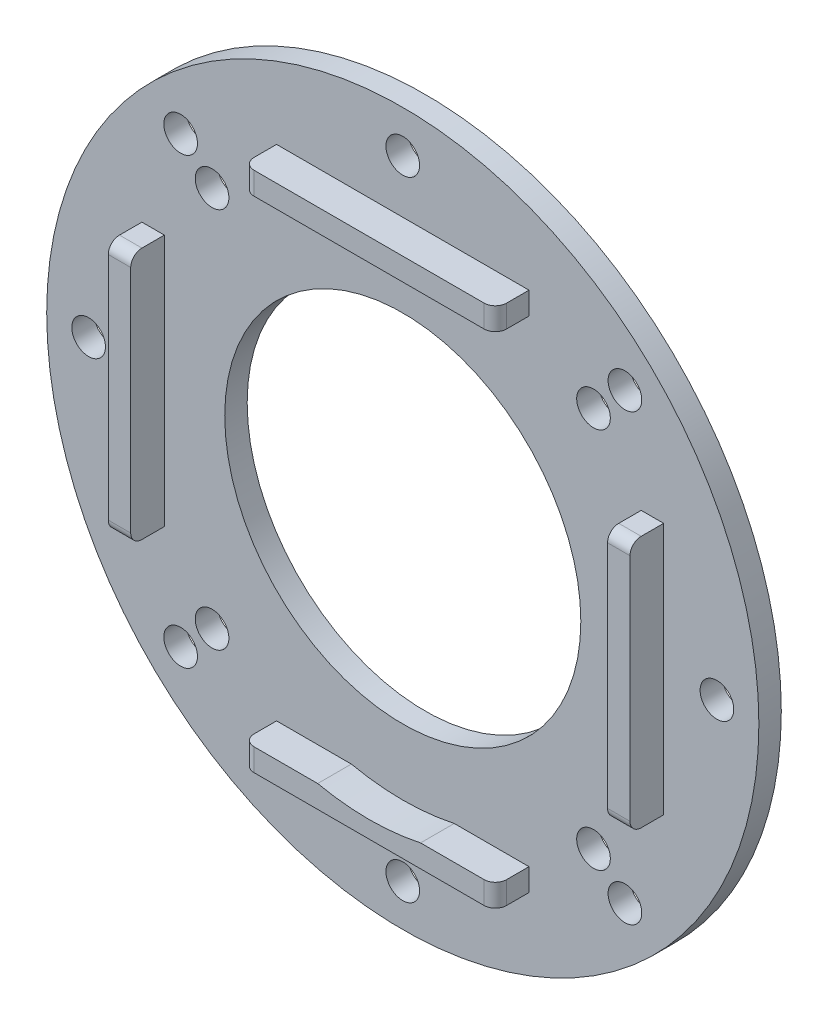
SolidWorks part; units mm, degrees
ref_plane "前视基准面" through (0, 0, 0) normal (0, 0, 1) x (1, 0, 0)
ref_plane "上视基准面" through (0, 0, 0) normal (0, 1, 0) x (1, 0, 0)
ref_plane "右视基准面" through (0, 0, 0) normal (1, 0, 0) x (0, 0, -1)
other "Configuration Table"
sketch "草图1" plane through (0, 0, 0) normal (0, 0, 1) x (1, 0, 0)
  line L1 (-17, -17) -> (17, -17)
  line L2 (-17, -17) -> (-17, 17)
  line L3 (-17, 17) -> (17, 17)
  line L4 (17, -17) -> (17, 17)
  line L5 (-17, -17) -> (17, 17) construction
  line L6 (-17, 17) -> (17, -17) construction
  circle A0 centre (0, 0) radius 31.739
  circle A1 centre (0, 0) radius 15.8695
  circle A2 centre (-17, 17) radius 1.5
  circle A3 centre (17, 17) radius 1.5
  circle A4 centre (17, -17) radius 1.5
  circle A5 centre (-17, -17) radius 1.5
  circle A6 centre (-19.799, 19.799) radius 1.5
  circle A7 centre (0, 28) radius 1.5
  circle A8 centre (19.799, 19.799) radius 1.5
  circle A9 centre (28, 0) radius 1.5
  circle A10 centre (19.799, -19.799) radius 1.5
  circle A11 centre (0, -28) radius 1.5
  circle A12 centre (-19.799, -19.799) radius 1.5
  circle A13 centre (-28, 0) radius 1.5
  point P18 (0, 0)
  point P36 (0, 0)
  dimension "D3" = 4
  dimension "D1" = 34
  dimension "D2" = 34
  dimension "D4" = 8
extrude "凸台-拉伸2" add sketch "草图1" along normal blind 2 contours A0 A13 A12 A11 A10 A9 A8 A7 A6 A5 L2 A2 L3 A3 L4 A4 L1 | A5 L1 A4 L4 A3 L3 A2 L2 A1
sketch "草图2" plane through (0, 0, 2) normal (0, 0, 1) x (1, 0, 0)
  line L0 (-23.25, -23.25) -> (-23.25, 23.25)
  line L1 (-21.25, -21.25) -> (21.25, -21.25)
  line L2 (-21.25, -21.25) -> (-21.25, 21.25)
  line L3 (-21.25, 21.25) -> (21.25, 21.25)
  line L4 (21.25, -21.25) -> (21.25, 21.25)
  line L5 (-21.25, -21.25) -> (21.25, 21.25) construction
  line L6 (-21.25, 21.25) -> (21.25, -21.25) construction
  line L7 (-23.25, 23.25) -> (23.25, 23.25)
  line L8 (23.25, -23.25) -> (23.25, 23.25)
  line L9 (-23.25, -23.25) -> (23.25, -23.25)
  line L10 (-21.25, 21.25) -> (-11.25, 21.25)
  line L11 (-11.25, 21.25) -> (-11.25, 23.25)
  line L12 (21.25, 21.25) -> (11.25, 21.25)
  line L13 (11.25, 21.25) -> (11.25, 23.25)
  line L14 (21.25, 11.25) -> (23.25, 11.25)
  line L15 (23.25, 23.25) -> (23.25, -23.25)
  line L16 (21.25, 21.25) -> (21.25, -21.25)
  line L17 (21.25, -11.25) -> (23.25, -11.25)
  line L18 (11.25, -21.25) -> (11.25, -23.25)
  line L19 (23.25, -23.25) -> (-23.25, -23.25)
  line L20 (21.25, -21.25) -> (-21.25, -21.25)
  line L21 (-11.25, -21.25) -> (-11.25, -23.25)
  line L22 (-21.25, -11.25) -> (-23.25, -11.25)
  line L23 (-23.25, -23.25) -> (-23.25, 23.25)
  line L24 (-21.25, -21.25) -> (-21.25, 21.25)
  line L25 (-21.25, 11.25) -> (-23.25, 11.25)
  circle A2 centre (0, 0) radius 21.739
  circle A3 centre (0, 0) radius 21.739
  point P0 (0, 0)
  point P44 (0, 0)
  dimension "D1" = 42.5
  dimension "D2" = 42.5
  dimension "D4" = 2
  dimension "D5" = 10
  dimension "D6" = 10
  dimension "D3" = 10
  dimension "D7" = 4
extrude "凸台-拉伸3" add sketch "草图2" along normal blind 3 contours A3 L3 L13 L7 L11 | A3 L2 L25 L0 L22 | A3 L16 L17 L15 L14 | A3 L20 L21 L19 L18 | L24 A3 | L3 A3 | L4 A3
fillet "圆角1" radius 1 1 edges at (-22.25, -11.25, 5)
fillet "圆角2" radius 1 1 edges at (-22.25, 11.25, 5)
fillet "圆角3" radius 1 1 edges at (-11.25, 22.25, 5)
fillet "圆角4" radius 1 1 edges at (11.25, 22.25, 5)
fillet "圆角5" radius 1 1 edges at (22.25, 11.25, 5)
fillet "圆角6" radius 1 1 edges at (22.25, -11.25, 5)
fillet "圆角7" radius 1 1 edges at (11.25, -22.25, 5)
fillet "圆角8" radius 1 1 edges at (-11.25, -22.25, 5)
